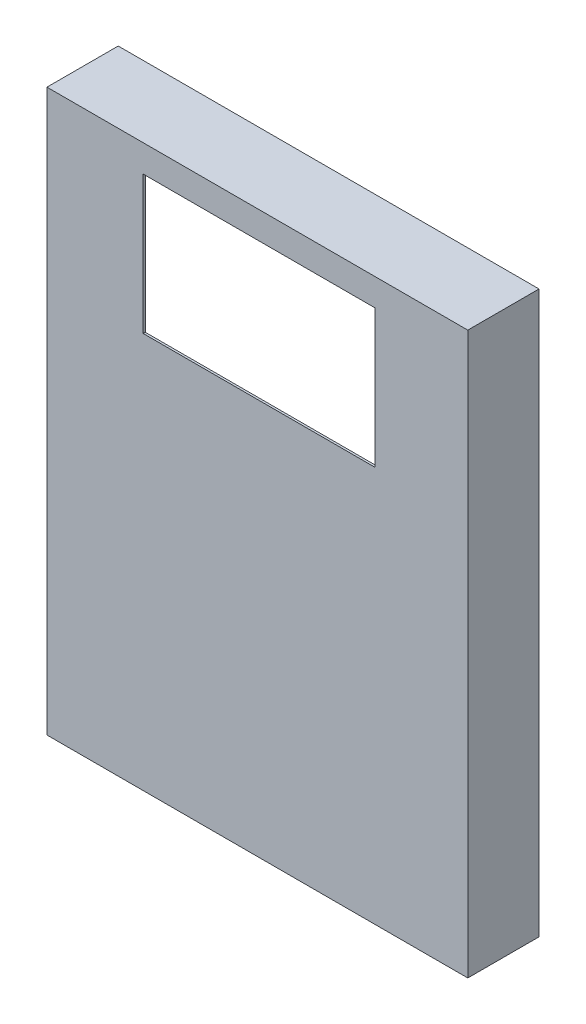
SolidWorks part; units mm, degrees
ref_plane "Front Plane" through (0, 0, 0) normal (0, 0, 1) x (1, 0, 0)
ref_plane "Top Plane" through (0, 0, 0) normal (0, 1, 0) x (1, 0, 0)
ref_plane "Right Plane" through (0, 0, 0) normal (1, 0, 0) x (0, 0, -1)
sketch "Sketch1" plane through (0, 0, 0) normal (0, 0, 1) x (1, 0, 0)
  line L1 (-150, -200) -> (150, -200)
  line L2 (-150, -200) -> (-150, 200)
  line L3 (-150, 200) -> (150, 200)
  line L4 (150, -200) -> (150, 200)
  line L5 (-150, -200) -> (150, 200) construction
  line L6 (-150, 200) -> (150, -200) construction
  point P0 (0, 0)
  dimension "D1" = 400
  dimension "D2" = 300
extrude "Boss-Extrude1" add sketch "Sketch1" along normal blind 50.8
shell "Shell1" thickness 1.5
sketch "Sketch2" plane through (0, 0, 50.8) normal (0, 0, 1) x (1, 0, 0)
  line L1 (-81.3989, 180.6434) -> (83.7011, 180.6434)
  line L2 (-81.3989, 180.6434) -> (-81.3989, 82.2184)
  line L3 (-81.3989, 82.2184) -> (83.7011, 82.2184)
  line L4 (83.7011, 180.6434) -> (83.7011, 82.2184)
  dimension "D1" = 98.425
  dimension "D2" = 165.1
extrude "Cut-Extrude1" cut sketch "Sketch2" against normal through all contours L1 L4 L3 L2
